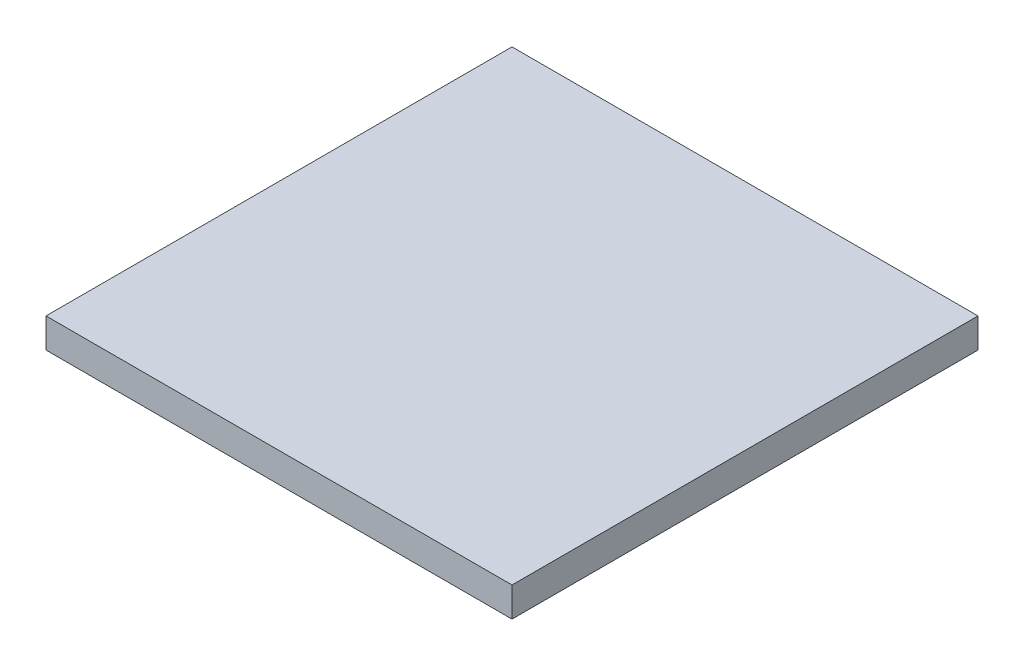
SolidWorks part; units mm, degrees
ref_plane "Front Plane" through (0, 0, 0) normal (0, 0, 1) x (1, 0, 0)
ref_plane "Top Plane" through (0, 0, 0) normal (0, 1, 0) x (1, 0, 0)
ref_plane "Right Plane" through (0, 0, 0) normal (1, 0, 0) x (0, 0, -1)
sketch "Sketch1" plane through (0, 0, 0) normal (0, 1, 0) x (1, 0, 0)
  line L1 (0, 0) -> (300, 0)
  line L2 (0, 0) -> (0, 300)
  line L3 (0, 300) -> (300, 300)
  line L4 (300, 0) -> (300, 300)
  dimension "D1" = 300
  dimension "D2" = 300
extrude "Boss-Extrude1" add sketch "Sketch1" along normal blind 19.05
